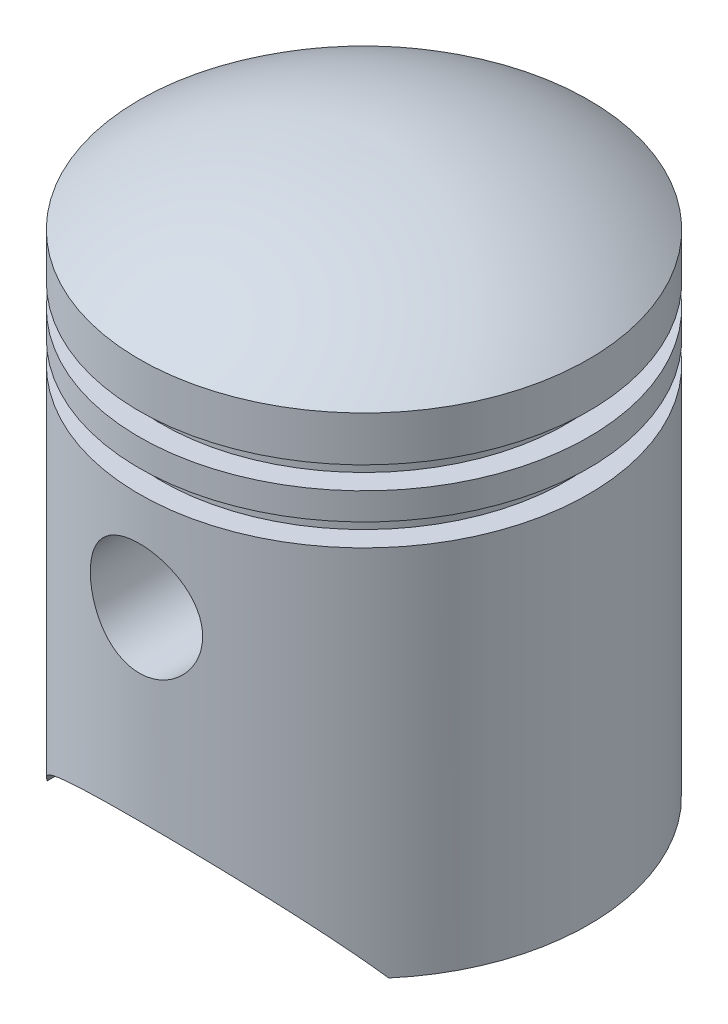
SolidWorks part; units mm, degrees
ref_plane "Front Plane" through (0, 0, 0) normal (0, 0, 1) x (1, 0, 0)
ref_plane "Top Plane" through (0, 0, 0) normal (0, 1, 0) x (1, 0, 0)
ref_plane "Right Plane" through (0, 0, 0) normal (1, 0, 0) x (0, 0, -1)
sketch "Sketch1" plane through (0, 0, 0) normal (0, 0, 1) x (1, 0, 0)
  line L0 (25, 0) -> (25, 41.5)
  line L1 (25, 49.5) -> (22.5, 49.5)
  line L2 (22.5, 49.5) -> (22.5, 47)
  line L3 (22.5, 47) -> (25, 47)
  line L4 (25, 44) -> (22.5, 44)
  line L5 (22.5, 44) -> (22.5, 41.5)
  line L6 (22.5, 41.5) -> (25, 41.5)
  line L7 (25, 49.5) -> (25, 54.5)
  line L8 (25, 44) -> (25, 47)
  line L9 (23, 0) -> (23, 39.5)
  line L10 (20.5, 39.5) -> (23, 39.5)
  line L11 (20.5, 45.5) -> (20.5, 39.5)
  line L12 (20.5, 45.5) -> (20.5, 45.5)
  line L13 (20.5, 45.5) -> (20.5, 45.5)
  line L14 (20.5, 45.5) -> (20.5, 45.5)
  line L15 (20.5, 51.5) -> (20.5, 45.5)
  line L16 (23, 51.5) -> (20.5, 51.5)
  line L17 (23, 51.5) -> (23, 53.4845)
  line L18 (25, 0) -> (23, 0)
  line L19 (0, 62.5) -> (0, 60.4994)
  arc A0 (25, 54.5) -> (0, 62.5) centre (0.9839, 22.5121) ccw
  arc A1 (23, 53.4845) -> (0, 60.4994) centre (0.9839, 22.5121) ccw
  arc A2 (23, 53.4845) -> (0.0492, 60.5006) centre (0.9839, 22.5121) ccw construction
  dimension "D4" = 40
  dimension "D1" = 25
  dimension "D2" = 62.5
  dimension "D3" = 54.5
  dimension "D5" = 5
  dimension "D6" = 2.5
  dimension "D7" = 2.5
  dimension "D8" = 3
  dimension "D9" = 2.5
  dimension "D10" = 2
revolve "Revolve1" add sketch "Sketch1" angle 360 about L19
sketch "Sketch2" plane through (0, 0, 0) normal (0, 0, 1) x (1, 0, 0)
  line L1 (-25, 0) -> (25, 0) construction
  line L2 (-19, 0) -> (19, 0)
  circle A0 centre (0, 30.5) radius 6.25
  arc A1 (-19, 0) -> (19, 0) centre (0, -13.05) cw
  point P5 (0, 10)
  dimension "D1" = 12.5
  dimension "D2" = 38
  dimension "D3" = 10
  dimension "D4" = 32
extrude "Cut-Extrude1" cut sketch "Sketch2" against normal through all both and the other way through all
sketch "Sketch3" plane through (0, 0, 0) normal (0, 0, 1) x (1, 0, 0)
  circle A0 centre (0, 30.5) radius 7.25
  circle A1 centre (0, 30.5) radius 6.25
  dimension "D1" = 14.5
  dimension "D2" = 12.5
extrude "Boss-Extrude3" add sketch "Sketch3" along normal up to surface (11.9257 mm away) from offset 12
mirror "Mirror2" about plane through (0, 0, 0) normal (0, 0, 1) of "Boss-Extrude3"
